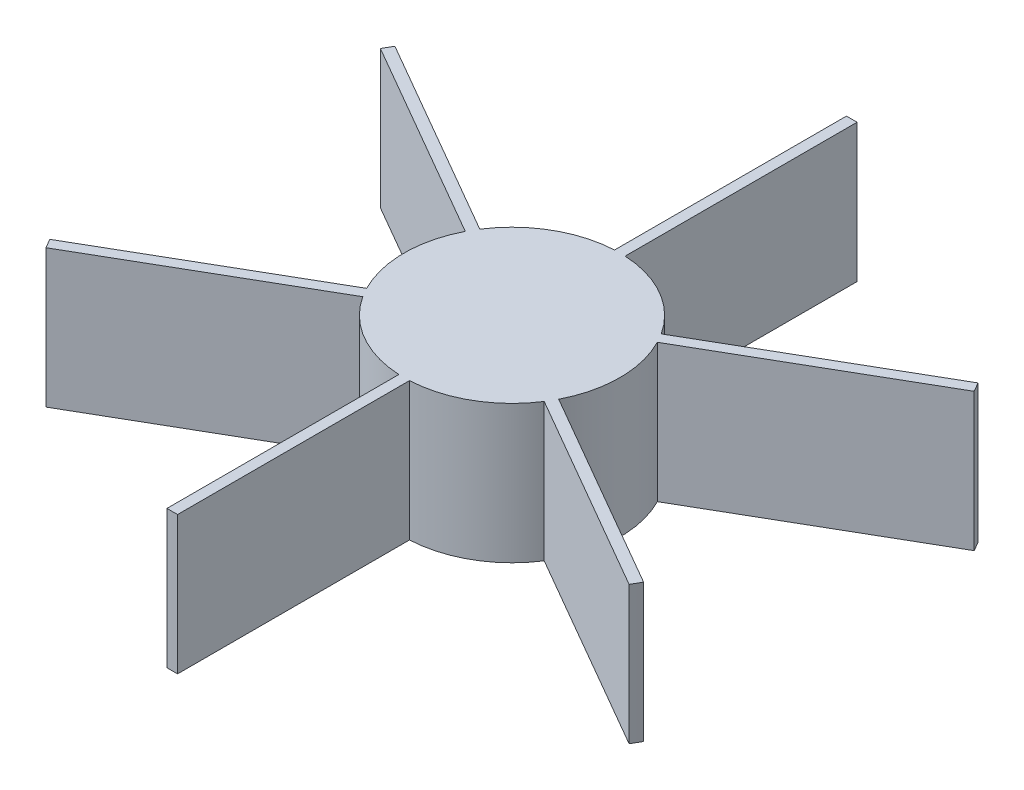
SolidWorks part; units mm, degrees
ref_plane "前视基准面" through (0, 0, 0) normal (0, 0, 1) x (1, 0, 0)
ref_plane "上视基准面" through (0, 0, 0) normal (0, 1, 0) x (1, 0, 0)
ref_plane "右视基准面" through (0, 0, 0) normal (1, 0, 0) x (0, 0, -1)
other "Configuration Table"
sketch "草图1" plane through (0, 0, 0) normal (0, 1, 0) x (1, 0, 0)
  line L0 (0, 0) -> (0, 57.7104) construction
  line L1 (0, 0) -> (0, -78.5163) construction
  line L2 (0, 0) -> (69.267, 39.9913) construction
  line L3 (0, 0) -> (-62.9871, -36.3656) construction
  line L4 (0, 0) -> (100.8524, -58.2272) construction
  line L5 (0, 0) -> (-91.7984, 52.9998) construction
  line L7 (82.3783, -49.2932) -> (20.4278, -13.5261)
  line L8 (21.9278, -10.928) -> (83.8783, -46.6951)
  line L11 (83.8783, 46.6951) -> (21.9278, 10.928)
  line L12 (82.3783, 49.2932) -> (20.4278, 13.5261)
  line L13 (0.8745, 96) -> (1.5, 96)
  line L14 (1.5, 96) -> (1.5, 24.454)
  line L15 (0.8745, 96) -> (-1.5, 96)
  line L16 (-1.5, 96) -> (-1.5, 24.454)
  line L18 (-82.3783, 49.2932) -> (-20.4278, 13.5261)
  line L20 (-83.8783, 46.6951) -> (-21.9278, 10.928)
  line L22 (-82.3783, -49.2932) -> (-20.4278, -13.5261)
  line L24 (-83.8783, -46.6951) -> (-21.9278, -10.928)
  line L26 (-1.5, -95.9883) -> (-1.5, -24.454)
  line L28 (1.5, -95.9883) -> (1.5, -24.454)
  circle A0 centre (0, 0) radius 20.5
  arc A7 (-82.3783, 49.2932) -> (-83.8783, 46.6951) centre (0, 0) ccw
  arc A8 (-83.8783, -46.6951) -> (-82.3783, -49.2932) centre (0, 0) ccw
  arc A9 (-1.5, -95.9883) -> (1.5, -95.9883) centre (0, 0) ccw
  arc A10 (83.8783, -46.6951) -> (82.3783, -49.2932) centre (0, 0) cw
  arc A11 (82.3783, 49.2932) -> (83.8783, 46.6951) centre (0, 0) cw
  arc A12 (21.9278, -10.928) -> (21.9278, 10.928) centre (0, 0) ccw
  arc A13 (20.4278, 13.5261) -> (1.5, 24.454) centre (0, 0) ccw
  arc A14 (-1.5, 24.454) -> (-20.4278, 13.5261) centre (0, 0) ccw
  arc A15 (-21.9278, 10.928) -> (-21.9278, -10.928) centre (0, 0) ccw
  arc A16 (-20.4278, -13.5261) -> (-1.5, -24.454) centre (0, 0) ccw
  arc A17 (1.5, -24.454) -> (20.4278, -13.5261) centre (0, 0) ccw
  point P20 (-0.3128, 96)
  point P33 (100.8524, -58.2272)
  dimension "D1" = 41
  dimension "D11" = 96
  dimension "D17" = 96
  dimension "D18" = 96
  dimension "D13" = 96
  dimension "D21" = 4
  dimension "D3" = 60
  dimension "D4" = 60
  dimension "D5" = 60
  dimension "D6" = 60
  dimension "D7" = 1.5
  dimension "D8" = 1.5
  dimension "D9" = 96
  dimension "D10" = 1.5
  dimension "D12" = 1.5
  dimension "D14" = 1.5
  dimension "D15" = 1.5
  dimension "D16" = 96
  dimension "D19" = 1.5
  dimension "D20" = 1.5
  dimension "D22" = 1.5
  dimension "D23" = 1.5
  dimension "D25" = 1.5
  dimension "D26" = 1.5
extrude "凸台-拉伸1" add sketch "草图1" along normal blind 40
sketch "草图2" plane through (0, 0, 0) normal (0, -1, 0) x (1, 0, 0)
  circle A0 centre (0, 0) radius 21
  dimension "D1" = 42
extrude "凸台-拉伸2" add sketch "草图2" against normal blind 35
sketch "草图4" plane through (0, 0, 0) normal (0, -1, 0) x (1, 0, 0)
  circle A0 centre (0, 0) radius 20.75
  dimension "D1" = 41.5
extrude "切除-拉伸2" cut sketch "草图4" against normal blind 28.5
sketch "草图6" plane through (0, 28.5, 0) normal (0, -1, 0) x (1, 0, 0)
  line L0 (0, 0) -> (0, 17) construction
  line L3 (0, 0) -> (0, -20) construction
  line L4 (0, 0) -> (-8.35, 0) construction
  line L5 (0, 0) -> (8.35, 0) construction
  line L6 (-6.4, 1.95) -> (0, 1.95) construction
  line L8 (-6.4, 1.95) -> (-6.4, 0) construction
  line L9 (-3.5, -1.95) -> (-6.4, -1.95) construction
  line L10 (0, 1.95) -> (6.4, 1.95) construction
  line L11 (6.4, 1.95) -> (6.4, 0) construction
  line L12 (3.5, -1.95) -> (6.4, -1.95) construction
  line L13 (-3.5, -1.95) -> (-2.1, -17.9) construction
  line L14 (2.1, -17.9) -> (3.5, -1.95) construction
  line L16 (2.9, 1.95) -> (2.1, 14.9) construction
  line L17 (-2.1, 14.9) -> (-2.9, 1.95) construction
  line L18 (-6.4, 1.95) -> (-2.9, 1.95) construction
  line L19 (2.9, 1.95) -> (6.4, 1.95) construction
  line L20 (-6.4, 1.95) -> (-2.9, 1.95)
  line L21 (-2.9, 1.95) -> (-2.1, 14.9)
  line L22 (2.1, 14.9) -> (2.9, 1.95)
  line L23 (2.9, 1.95) -> (6.4, 1.95)
  line L24 (6.4, -1.95) -> (3.5, -1.95)
  line L25 (3.5, -1.95) -> (2.1, -17.9)
  line L26 (-2.1, -17.9) -> (-3.5, -1.95)
  line L27 (-3.5, -1.95) -> (-6.4, -1.95)
  arc A0 (-6.4, 1.95) -> (-6.4, -1.95) centre (-6.4, 0) ccw
  arc A1 (6.4, 1.95) -> (6.4, -1.95) centre (6.4, 0) cw
  arc A2 (-2.1, -17.9) -> (2.1, -17.9) centre (0, -17.9) ccw
  arc A3 (2.1, 14.9) -> (-2.1, 14.9) centre (0, 14.9) ccw
  dimension "D1" = 2.1
  dimension "D6" = 3.5
  dimension "D9" = 2.1
  dimension "D15" = 2.1
  dimension "D2" = 16.7
  dimension "D3" = 1.95
  dimension "D4" = 6.4
  dimension "D5" = 6.4
  dimension "D7" = 20
  dimension "D10" = 3.5
  dimension "D11" = 2.1
  dimension "D12" = 2.9
  dimension "D13" = 17
  dimension "D14" = 2.1
  dimension "D16" = 2.9
  dimension "D17" = 4.2
  dimension "D18" = 37
extrude "切除-拉伸3" cut sketch "草图6" against normal blind 17
sketch "草图7" plane through (0, 40, 0) normal (0, 1, 0) x (1, 0, 0)
  circle A0 centre (0, 0) radius 30.5
  circle A1 centre (0, 0) radius 24.5
  dimension "D1" = 61
extrude "凸台-拉伸4" add sketch "草图7" against normal blind 40 contours A1 | A0
sketch "草图8" plane through (0, 0, 0) normal (0, -1, 0) x (1, 0, 0)
  circle A0 centre (0, 0) radius 27
  arc A1 (27.1318, -13.9325) -> (27.1318, 13.9325) centre (0, 0) ccw construction
  circle A2 centre (0, 0) radius 20.75
  dimension "D1" = 3.5
extrude "切除-拉伸4" cut sketch "草图8" against normal blind 30
sketch "草图9" plane through (0, 35, 0) normal (0, 1, 0) x (1, 0, 0)
  circle A0 centre (0, 0) radius 20.5
extrude "凸台-拉伸5" add sketch "草图9" along normal blind 5
sketch "草图11" plane through (0, 0, 0) normal (0, -1, 0) x (1, 0, 0)
  circle A0 centre (0, 0) radius 155.05
extrude "切除-拉伸5" cut sketch "草图11" against normal blind 1
sketch "草图12" plane through (0, 1, 0) normal (0, -1, 0) x (1, 0, 0)
  line L0 (-1.5, -96) -> (3, -96)
  line L1 (3, -96) -> (3, -30.3521)
  line L2 (3, -30.3521) -> (-3, -30.3521)
  line L3 (-3, -30.3521) -> (-3, -96)
  line L4 (-3, -96) -> (-1.5, -96)
  line L7 (1.5, -96) -> (1.5, -30.4631) construction
  line L8 (82.3783, -49.2932) -> (84.6283, -45.3961)
  line L9 (84.6283, -45.3961) -> (27.7857, -12.578)
  line L10 (27.7857, -12.578) -> (24.7857, -17.7741)
  line L11 (24.7857, -17.7741) -> (81.6283, -50.5922)
  line L12 (81.6283, -50.5922) -> (82.3783, -49.2932)
  line L13 (25.6318, -16.5306) -> (82.3783, -49.2932) construction
  line L14 (83.8783, -46.6951) -> (27.1318, -13.9325) construction
  arc A0 (1.5, -30.4631) -> (25.6318, -16.5306) centre (0, 0) ccw construction
  arc A1 (-25.6318, -16.5306) -> (-1.5, -30.4631) centre (0, 0) ccw construction
  arc A2 (27.1318, -13.9325) -> (27.1318, 13.9325) centre (0, 0) ccw construction
  dimension "D1" = 6
  dimension "D2" = 1.5
  dimension "D3" = 90
  dimension "D4" = 90
  dimension "D5" = 180
  dimension "D6" = 1.5
  dimension "D7" = 1.5
